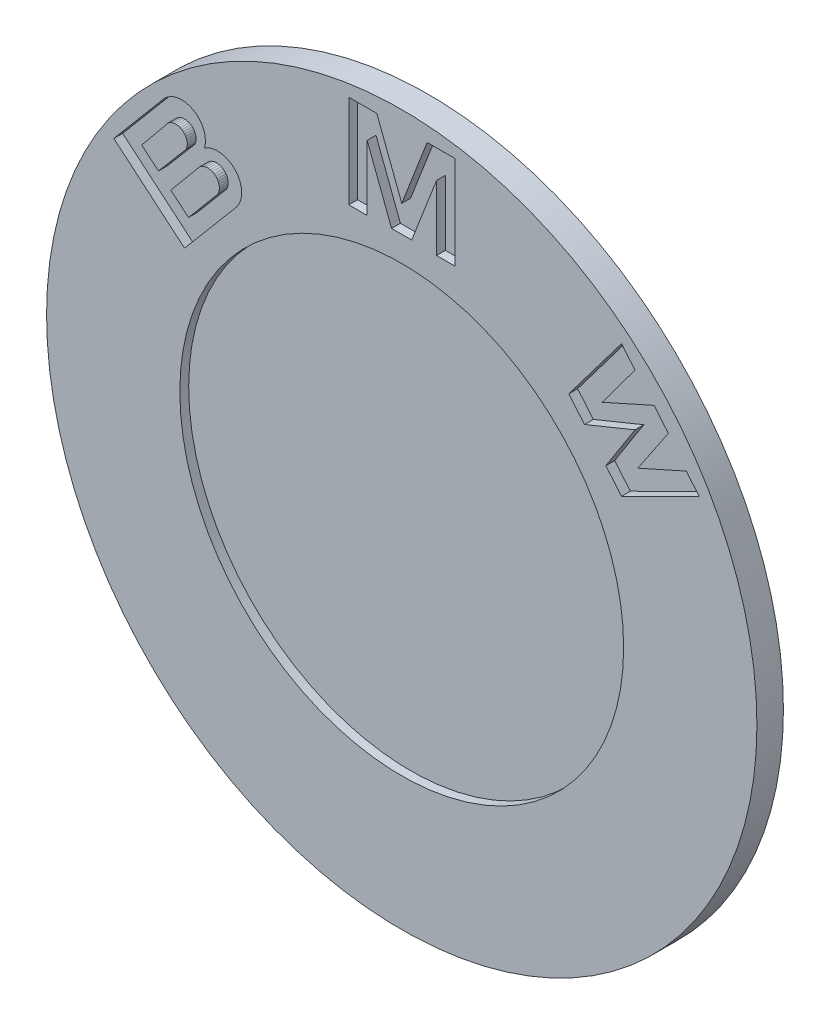
SolidWorks part; units mm, degrees
ref_plane "前视基准面" through (0, 0, 0) normal (0, 0, 1) x (1, 0, 0)
ref_plane "上视基准面" through (0, 0, 0) normal (0, 1, 0) x (1, 0, 0)
ref_plane "右视基准面" through (0, 0, 0) normal (1, 0, 0) x (0, 0, -1)
other "Configuration Table"
sketch "草图1" plane through (0, 0, 0) normal (0, 0, 1) x (1, 0, 0)
  circle A0 centre (0, 0) radius 40.2
  dimension "D1" = 80.4
extrude "凸台-拉伸1" add sketch "草图1" along normal blind 3
sketch "草图4" plane through (0, 0, 3) normal (0, 0, 1) x (1, 0, 0)
  line L0 (-32.5858, 21.0675) -> (-24.5818, 14.3186)
  line L1 (-24.5818, 14.3186) -> (-18.6672, 21.3331)
  line L2 (-32.5858, 21.0675) -> (-26.8673, 27.8598)
  line L3 (-29.4331, 22.0067) -> (-27.5368, 20.4017)
  line L4 (-27.5368, 20.4017) -> (-24.4154, 24.0896)
  line L5 (-29.4331, 22.0067) -> (-26.7287, 25.2829)
  line L7 (-22.928, 23.0862) -> (-26.1312, 19.23)
  line L8 (-26.1312, 19.23) -> (-24.1325, 17.5488)
  line L9 (-24.1325, 17.5488) -> (-20.8446, 21.4575)
  line L10 (-5.9969, 38.4089) -> (-5.9969, 27.8598)
  line L11 (-5.9969, 27.8598) -> (-3.9128, 27.8598)
  line L12 (-3.9128, 27.8598) -> (-3.9128, 35.2187)
  line L13 (-3.9128, 35.2187) -> (-1.1506, 27.9722)
  line L14 (-1.1506, 27.9722) -> (1.1264, 27.9722)
  line L15 (1.1264, 27.9722) -> (3.9398, 35.2187)
  line L16 (3.9398, 35.2187) -> (3.9398, 27.8598)
  line L17 (3.9398, 27.8598) -> (6.0143, 27.8598)
  line L18 (6.0143, 27.8598) -> (6.0143, 38.4089)
  line L19 (6.0143, 38.4089) -> (2.8764, 38.4089)
  line L20 (2.8764, 38.4089) -> (0, 31)
  line L21 (0, 31) -> (-2.8241, 38.4089)
  line L22 (-2.8241, 38.4089) -> (-5.9969, 38.4089)
  line L23 (24.8728, 29.6874) -> (26.4029, 27.8598)
  line L24 (26.4029, 27.8598) -> (22.6901, 22.8517)
  line L25 (22.6901, 22.8517) -> (28.5582, 25.4792)
  line L26 (28.5582, 25.4792) -> (30.1753, 23.5477)
  line L27 (30.1753, 23.5477) -> (26.7186, 18.4048)
  line L28 (26.7186, 18.4048) -> (32.2027, 20.8603)
  line L29 (32.2027, 20.8603) -> (33.6836, 19.0914)
  line L30 (33.6836, 19.0914) -> (24.8728, 14.7236)
  line L31 (24.8728, 14.7236) -> (23.0998, 16.8414)
  line L32 (23.0998, 16.8414) -> (26.4029, 22.0067)
  line L33 (26.4029, 22.0067) -> (20.6841, 19.668)
  line L34 (20.6841, 19.668) -> (18.9093, 21.7879)
  line L35 (18.9093, 21.7879) -> (24.8728, 29.6874)
  line L36 (-26.8673, 27.8598) -> (-26.5349, 28.1583)
  line L37 (-26.5349, 28.1583) -> (-26.1576, 28.3976)
  line L38 (-26.1576, 28.3976) -> (-25.746, 28.5711)
  line L39 (-25.746, 28.5711) -> (-25.3112, 28.6741)
  line L40 (-25.3112, 28.6741) -> (-24.8655, 28.7036)
  line L41 (-24.8655, 28.7036) -> (-24.421, 28.659)
  line L42 (-24.421, 28.659) -> (-23.99, 28.5414)
  line L43 (-23.99, 28.5414) -> (-23.5844, 28.3541)
  line L44 (-23.5844, 28.3541) -> (-23.2155, 28.1022)
  line L45 (-23.2155, 28.1022) -> (-22.8933, 27.7926)
  line L46 (-22.8933, 27.7926) -> (-22.6268, 27.4341)
  line L47 (-22.6268, 27.4341) -> (-22.4234, 27.0363)
  line L48 (-22.4234, 27.0363) -> (-22.2886, 26.6104)
  line L49 (-22.2886, 26.6104) -> (-22.2262, 26.168)
  line L50 (-22.2262, 26.168) -> (-22.2379, 25.7214)
  line L51 (-22.2379, 25.7214) -> (-22.3234, 25.2829)
  line L52 (-22.3234, 25.2829) -> (-21.9021, 25.5042)
  line L53 (-21.9021, 25.5042) -> (-21.4487, 25.649)
  line L54 (-21.4487, 25.649) -> (-20.9771, 25.713)
  line L55 (-20.9771, 25.713) -> (-20.5015, 25.6942)
  line L56 (-20.5015, 25.6942) -> (-20.0365, 25.5932)
  line L57 (-20.0365, 25.5932) -> (-19.5959, 25.4131)
  line L58 (-19.5959, 25.4131) -> (-19.1933, 25.1593)
  line L59 (-19.1933, 25.1593) -> (-18.8409, 24.8395)
  line L60 (-18.8409, 24.8395) -> (-18.5492, 24.4634)
  line L61 (-18.5492, 24.4634) -> (-18.3272, 24.0424)
  line L62 (-18.3272, 24.0424) -> (-18.1816, 23.5893)
  line L63 (-18.1816, 23.5893) -> (-18.1167, 23.1178)
  line L64 (-18.1167, 23.1178) -> (-18.1347, 22.6423)
  line L65 (-18.1347, 22.6423) -> (-18.2348, 22.177)
  line L66 (-18.2348, 22.177) -> (-18.4141, 21.7362)
  line L67 (-18.4141, 21.7362) -> (-18.6672, 21.3331)
  line L68 (-26.7287, 25.2829) -> (-26.6147, 25.4652)
  line L69 (-26.6147, 25.4652) -> (-26.4723, 25.6262)
  line L70 (-26.4723, 25.6262) -> (-26.3053, 25.7615)
  line L71 (-26.3053, 25.7615) -> (-26.1183, 25.8676)
  line L72 (-26.1183, 25.8676) -> (-25.9164, 25.9414)
  line L73 (-25.9164, 25.9414) -> (-25.7052, 25.9809)
  line L74 (-25.7052, 25.9809) -> (-25.4902, 25.9852)
  line L75 (-25.4902, 25.9852) -> (-25.2776, 25.954)
  line L76 (-25.2776, 25.954) -> (-25.0729, 25.8882)
  line L77 (-25.0729, 25.8882) -> (-24.8819, 25.7897)
  line L78 (-24.8819, 25.7897) -> (-24.7097, 25.661)
  line L79 (-24.7097, 25.661) -> (-24.561, 25.5058)
  line L80 (-24.561, 25.5058) -> (-24.4399, 25.3282)
  line L81 (-24.4399, 25.3282) -> (-24.3497, 25.1331)
  line L82 (-24.3497, 25.1331) -> (-24.2928, 24.9258)
  line L83 (-24.2928, 24.9258) -> (-24.2708, 24.712)
  line L84 (-24.2708, 24.712) -> (-24.2843, 24.4975)
  line L85 (-24.2843, 24.4975) -> (-24.3329, 24.2881)
  line L86 (-24.3329, 24.2881) -> (-24.4154, 24.0896)
  line L87 (-22.928, 23.0862) -> (-22.7556, 23.239)
  line L88 (-22.7556, 23.239) -> (-22.5595, 23.3597)
  line L89 (-22.5595, 23.3597) -> (-22.3455, 23.4447)
  line L90 (-22.3455, 23.4447) -> (-22.12, 23.4915)
  line L91 (-22.12, 23.4915) -> (-21.8898, 23.4986)
  line L92 (-21.8898, 23.4986) -> (-21.6619, 23.4658)
  line L93 (-21.6619, 23.4658) -> (-21.443, 23.3942)
  line L94 (-21.443, 23.3942) -> (-21.2398, 23.2858)
  line L95 (-21.2398, 23.2858) -> (-21.0583, 23.144)
  line L96 (-21.0583, 23.144) -> (-20.9041, 22.973)
  line L97 (-20.9041, 22.973) -> (-20.7818, 22.7778)
  line L98 (-20.7818, 22.7778) -> (-20.695, 22.5645)
  line L99 (-20.695, 22.5645) -> (-20.6463, 22.3394)
  line L100 (-20.6463, 22.3394) -> (-20.6373, 22.1093)
  line L101 (-20.6373, 22.1093) -> (-20.6681, 21.8811)
  line L102 (-20.6681, 21.8811) -> (-20.7379, 21.6616)
  line L103 (-20.7379, 21.6616) -> (-20.8446, 21.4575)
  point P3 (0, 0)
extrude "切除-拉伸2" cut sketch "草图4" against normal blind 1
sketch "草图2" plane through (0, 0, 0) normal (0, 0, -1) x (-1, 0, 0)
  circle A0 centre (0, 0) radius 25.115
  dimension "D1" = 50.23
extrude "切除-拉伸1" cut sketch "草图2" along normal blind 1 from surface at -3 starting at face at (-22.1143, 25.4891, 3)
